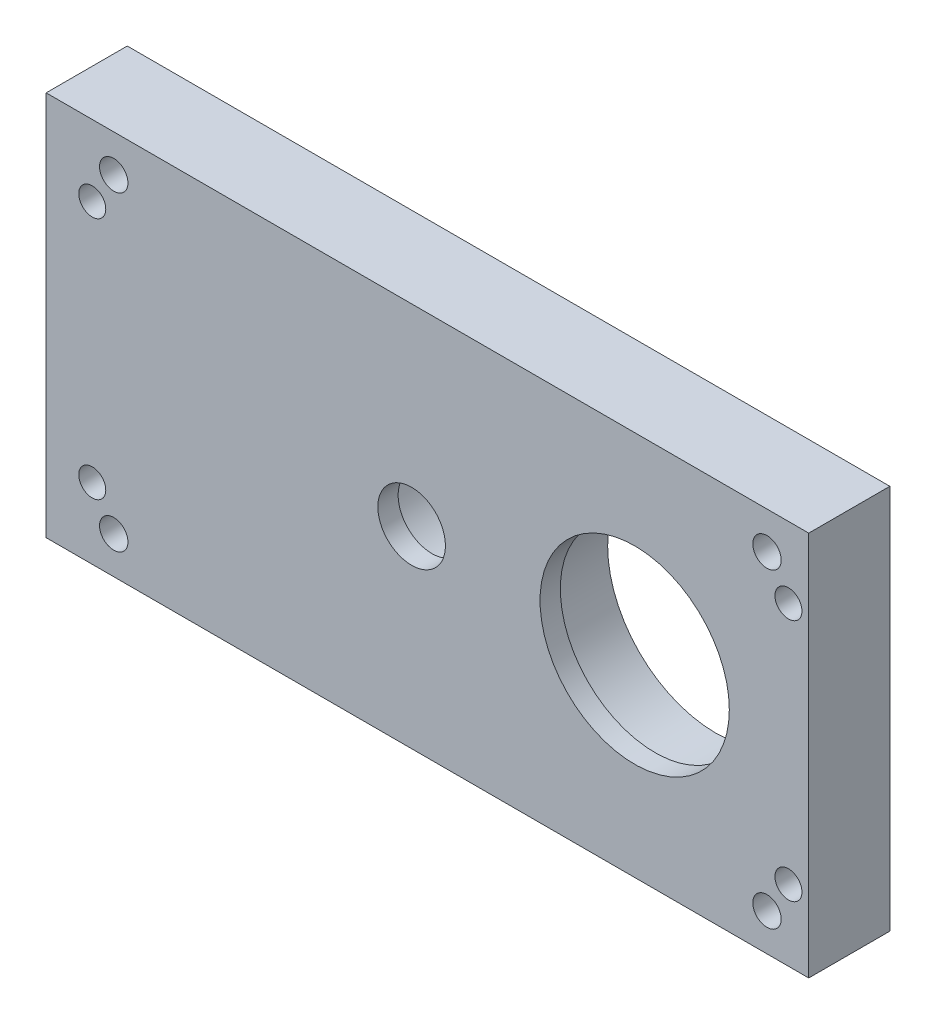
SolidWorks part; units mm, degrees
material "7075-T6, Chapa (SS)"
ref_plane "Plano frontal" through (0, 0, 0) normal (0, 0, 1) x (1, 0, 0)
ref_plane "Plano superior" through (0, 0, 0) normal (0, 1, 0) x (1, 0, 0)
ref_plane "Plano direito" through (0, 0, 0) normal (1, 0, 0) x (0, 0, -1)
sketch "Esboço1" plane through (0, 0, 0) normal (0, 0, 1) x (1, 0, 0)
  line L1 (-59, 31) -> (59, 31)
  line L2 (-59, 31) -> (-59, -31)
  line L3 (-59, -31) -> (59, -31)
  line L4 (59, 31) -> (59, -31)
  circle A0 centre (-4.25, 0) radius 9.5
  circle A1 centre (28.75, 0) radius 16
  circle A2 centre (51.5, -18) radius 2
  circle A3 centre (51.5, 18) radius 2
  circle A4 centre (-51.5, -18) radius 2
  circle A5 centre (-51.5, 18) radius 2
  dimension "D5" = 32
  dimension "D6" = 19
  dimension "D9" = 4
  dimension "D1" = 62
  dimension "D2" = 118
  dimension "D3" = 59
  dimension "D4" = 31
  dimension "D7" = 54.75
  dimension "D8" = 30.25
  dimension "D10" = 7.5
  dimension "D11" = 13
  dimension "D12" = 7.5
  dimension "D13" = 13
extrude "Ressalto-extrusão1" add sketch "Esboço1" along normal blind 12
hole_wizard "Furo com folga de M51" positions "Esboço11" profile "Esboço12" hole size "M5" standard "ISO" end condition through all
sketch "Esboço11" plane through (0, 0, 12) normal (0, 0, 1) x (1, 0, 0)
  line L0 (-48.32, 23) -> (-48.32, -23) construction
  line L1 (-48.32, -23) -> (48.32, -23) construction
  line L2 (48.32, -23) -> (48.32, 23) construction
  line L3 (48.32, 23) -> (-48.32, 23) construction
  line L5 (59, 31) -> (-59, 31) construction
  line L6 (-59, 31) -> (-59, -31) construction
  line L7 (-59, -31) -> (59, -31) construction
  line L8 (59, -31) -> (59, 31) construction
  point P1 (-48.32, 23)
  point P2 (-48.32, -23)
  point P4 (48.32, -23)
  point P5 (48.32, 23)
  dimension "D1" = 8
  dimension "D2" = 10.68
  dimension "D3" = 8
  dimension "D4" = 10.68
sketch "Esboço12" plane through (-48.32, 23, 12) normal (1, 0, 0) x (0, -1, 0)
  line L0 (0, 0) -> (0, 12)
  line L1 (0, 12) -> (2.1, 12)
  line L2 (2.1, 12) -> (2.1, 0)
  line L5 (2.1, 0) -> (0, 0)
  line L11 (0, -6.35) -> (0, 107.95) construction
  dimension "Thru Hole Dia." = 4.2
  dimension "Thru Hole Depth" = 12
sketch "Esboço17" plane through (0, 0, 12) normal (0, 0, 1) x (1, 0, 0)
  circle A0 centre (-4.25, 0) radius 9.5
  dimension "D1" = 19
extrude "Ressalto-extrusão4" add sketch "Esboço17" against normal blind 3
sketch "Esboço18" plane through (0, 0, 12) normal (0, 0, 1) x (1, 0, 0)
  line L0 (-58.32, 28.5) -> (-58.32, -28.5)
  line L1 (-58.32, -28.5) -> (54.5, -28.5)
  line L2 (54.5, -28.5) -> (54.5, 28.5)
  line L5 (59, 31) -> (59, -31)
  line L6 (59, -31) -> (-59, -31)
  line L7 (-59, -31) -> (-59, 31)
  line L9 (-58.32, 28.5) -> (54.5, 28.5)
  line L11 (59, 31) -> (-59, 31)
  dimension "D1" = 0.68
  dimension "D2" = 4.5
  dimension "D3" = 2.5
  dimension "D4" = 2.5
extrude "Corte-extrusão3" cut sketch "Esboço18" against normal through all
sketch "Esboço19" plane through (0, 0, 12) normal (0, 0, 1) x (1, 0, 0)
  circle A0 centre (28.75, 0) radius 16
  circle A1 centre (28.75, 0) radius 14
  dimension "D1" = 32
  dimension "D2" = 28
extrude "Ressalto-extrusão5" add sketch "Esboço19" against normal blind 3
sketch "Esboço21" plane through (0, 0, 9) normal (0, 0, -1) x (-1, 0, 0)
  circle A0 centre (4.25, 0) radius 5
  dimension "D1" = 10
extrude "Corte-extrusão4" cut sketch "Esboço21" against normal blind 10
